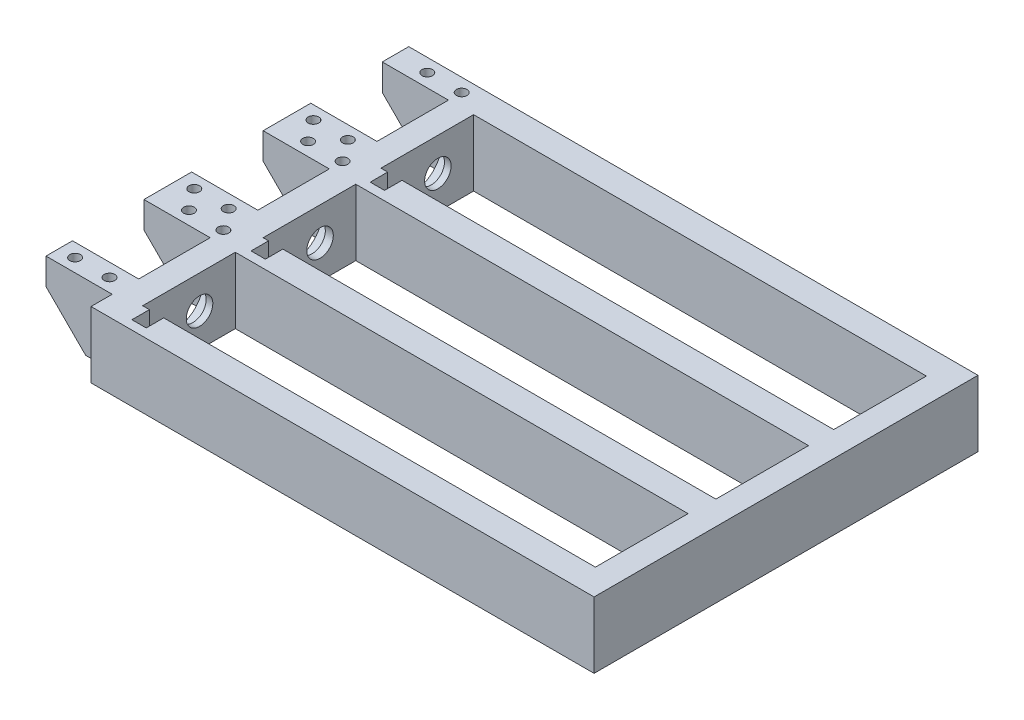
SolidWorks part; units mm, degrees
ref_plane "Płaszczyzna przednia" through (0, 0, 0) normal (0, 0, 1) x (1, 0, 0)
ref_plane "Płaszczyzna górna" through (0, 0, 0) normal (0, 1, 0) x (1, 0, 0)
ref_plane "Płaszczyzna prawa" through (0, 0, 0) normal (1, 0, 0) x (0, 0, -1)
sketch "Szkic1" plane through (0, 0, 0) normal (0, 1, 0) x (1, 0, 0)
  line L1 (-95, 72.5) -> (95, 72.5)
  line L2 (-95, 72.5) -> (-95, -72.5)
  line L3 (-95, -72.5) -> (95, -72.5)
  line L4 (95, 72.5) -> (95, -72.5)
  line L5 (-95, 72.5) -> (95, -72.5) construction
  line L6 (-95, -72.5) -> (95, 72.5) construction
  point P0 (0, 0)
  dimension "D1" = 145
  dimension "D2" = 190
extrude "Dodanie-wyciągnięcie1" add sketch "Szkic1" along normal blind 25
sketch "Szkic2" plane through (0, 25, 0) normal (0, 1, 0) x (1, 0, 0)
  line L0 (-95, 0) -> (95, 0) construction
  line L1 (-95, 72.5) -> (-95, -72.5) construction
  line L2 (95, -72.5) -> (95, 72.5) construction
  line L3 (0, 0) -> (0, -72.5) construction
  line L4 (-85, -17.5) -> (86, -17.5)
  line L5 (-85, -17.5) -> (-85, 17.5)
  line L6 (-85, 17.5) -> (86, 17.5)
  line L7 (86, -17.5) -> (86, 17.5)
  line L8 (-85, -17.5) -> (86, 17.5) construction
  line L9 (-85, 17.5) -> (86, -17.5) construction
  line L10 (-95, -72.5) -> (95, -72.5) construction
  line L11 (-85.5, 27.5) -> (85.5, 62.5) construction
  line L12 (-85.5, -62.5) -> (85.5, -62.5)
  line L13 (-85.5, -62.5) -> (-85.5, -27.5)
  line L14 (-85.5, -27.5) -> (85.5, -27.5)
  line L15 (85.5, -62.5) -> (85.5, -27.5)
  line L16 (-85.5, -62.5) -> (85.5, -27.5) construction
  line L17 (-85.5, -27.5) -> (85.5, -62.5) construction
  line L18 (-85.5, 62.5) -> (85.5, 27.5) construction
  line L19 (85.5, 62.5) -> (85.5, 27.5)
  line L20 (-85.5, 27.5) -> (85.5, 27.5)
  line L21 (-85.5, 62.5) -> (-85.5, 27.5)
  line L22 (-85.5, 62.5) -> (85.5, 62.5)
  point P6 (0.5, 0)
  point P15 (0, -45)
  point P24 (0, 45)
  dimension "D1" = 35
  dimension "D2" = 9
  dimension "D3" = 10
  dimension "D4" = 10
  dimension "D5" = 35
extrude "Wytnij-wyciągnięcie1" cut sketch "Szkic2" against normal blind 50
sketch "Szkic3" plane through (85.5, 0, 0) normal (-1, 0, 0) x (0, 0, 1)
  line L0 (27.5, 12.5) -> (62.5, 12.5) construction
  line L1 (27.5, 0) -> (27.5, 25) construction
  line L2 (62.5, 0) -> (62.5, 25) construction
  circle A0 centre (41, 12.5) radius 11
  dimension "D1" = 22
  dimension "D2" = 13.5
extrude "Wytnij-wyciągnięcie2" cut sketch "Szkic3" against normal blind 7
sketch "Szkic4" plane through (-95, 0, 0) normal (-1, 0, 0) x (0, 0, 1)
  circle A0 centre (41, 12.5) radius 11 construction
  circle A1 centre (41, 12.5) radius 11
extrude "Wytnij-wyciągnięcie3" cut sketch "Szkic4" against normal blind 7
sketch "Szkic5" plane through (-88, 0, 0) normal (-1, 0, 0) x (0, 0, 1)
  circle A0 centre (41, 12.5) radius 5
  dimension "D1" = 10
extrude "Wytnij-wyciągnięcie4" cut sketch "Szkic5" against normal blind 7
sketch "Szkic7" plane through (0, 25, 0) normal (0, 1, 0) x (1, 0, 0)
  line L0 (-95, 72.5) -> (-95, -72.5) construction
  line L1 (-95, -64.5) -> (-120, -64.5)
  line L2 (-95, -64.5) -> (-95, -54.5)
  line L3 (-95, -54.5) -> (-120, -54.5)
  line L4 (-120, -64.5) -> (-120, -54.5)
  line L6 (-95, -27.5) -> (-120, -27.5)
  line L7 (-95, -27.5) -> (-95, -17.5)
  line L8 (-95, -17.5) -> (-120, -17.5)
  line L9 (-120, -27.5) -> (-120, -17.5)
  line L10 (-85.5, -46) -> (-85.5, -36) construction
  line L11 (-85.5, -41) -> (-183.1039, -41) construction
  line L12 (-95, -27.5) -> (-95, -54.5) construction
  line L13 (95, -72.5) -> (95, 72.5) construction
  line L14 (-85.5, -46) -> (-85.5, -36)
  line L15 (-85.5, -41) -> (95, -41) construction
  point P14 (-95, -41)
  line M24 (-95, 72.5) -> (-95, -72.5)
  dimension "D1" = 27
  dimension "D2" = 10
  dimension "D3" = 215
extrude "Dodanie-wyciągnięcie2" add sketch "Szkic7" against normal up to vertex (25 mm away) contours L9 L6 L8 M24 | L4 L1 L3 M24 up to point (-95, 0, 72.5)
sketch "Szkic8" plane through (0, 25, 0) normal (0, 1, 0) x (1, 0, 0)
  line L0 (-120, -59.5) -> (-114, -59.5) construction
  line L1 (-120, -64.5) -> (-120, -54.5) construction
  line L3 (-95, -41) -> (-185.7611, -41) construction
  line L4 (-95, -27.5) -> (-95, -54.5) construction
  line L5 (-114, -59.5) -> (-101, -59.5) construction
  line L6 (-120, -22.5) -> (-108, -22.5) construction
  line L7 (-120, -27.5) -> (-120, -17.5) construction
  line L8 (-108, -22.5) -> (-95, -22.5) construction
  circle A0 centre (-114, -59.5) radius 2
  circle A1 centre (-101, -59.5) radius 2
  circle A6 centre (-108, -22.5) radius 2
  circle A7 centre (-95, -22.5) radius 2
  dimension "D2" = 13
  dimension "D3" = 6
  dimension "D1" = 4
  dimension "D4" = 13
  dimension "D5" = 12
extrude "Wytnij-wyciągnięcie5" cut sketch "Szkic8" against normal blind 12
sketch "Szkic10" plane through (0, 25, 0) normal (0, 1, 0) x (1, 0, 0)
  line L0 (-82.45, -66.4) -> (-82.95, -66.4) construction
  line L1 (-85.5, -62.5) -> (85.5, -62.5) construction
  line L7 (-80.25, -66.4) -> (-80.25, -60.0836) construction
  line L8 (-80.25, -69.1) -> (-80.25, -68.6) construction
  line L9 (-77.55, -62.5) -> (-82.95, -62.5)
  line L10 (-77.55, -62.5) -> (-77.55, -69.1)
  line L11 (-77.55, -69.1) -> (-82.95, -69.1)
  line L12 (-82.95, -62.5) -> (-82.95, -69.1)
  line L13 (-77.55, -62.5) -> (-82.95, -69.1) construction
  line L14 (-78.05, -62.35) -> (-78.05, -58.85)
  line L15 (-78.05, -58.85) -> (-82.45, -58.85)
  line L16 (-82.45, -58.85) -> (-82.45, -62.35)
  line L17 (-82.45, -62.35) -> (-81.075, -62.35)
  line L18 (-81.075, -62.35) -> (-81.075, -64.3605)
  line L19 (-79.425, -64.3605) -> (-79.425, -62.35)
  line L20 (-79.425, -62.35) -> (-78.05, -62.35)
  line L21 (-77.55, -69.1) -> (-82.95, -62.5) construction
  arc A2 (-81.075, -64.3605) -> (-79.425, -64.3605) centre (-80.25, -66.4) ccw
  point P4 (-80.25, -65.8)
  line M52 (85.5, -62.5) -> (-85.5, -62.5)
  dimension "D2" = 2.2
  dimension "D1" = 80.25
  dimension "D3" = 0.5
  dimension "D4" = 66.4
  dimension "D5" = 0.5
extrude "Wytnij-wyciągnięcie6" cut sketch "Szkic10" against normal blind 40 contours A2 L18 L9 L12 L11 L10 L19 M52 | L18 A2 L19 L9
pattern_linear "Szyk liniowy1" count 3 spacing 45 along (0, 0, -1) of "Wytnij-wyciągnięcie5", "Dodanie-wyciągnięcie2", "Wytnij-wyciągnięcie4", "Wytnij-wyciągnięcie3", "Wytnij-wyciągnięcie2", "Wytnij-wyciągnięcie6"
chamfer "Sfazowanie1" distance 15 angle 45 4 edges at (-120, 0, 59.5) (-120, 0, 18.5) (-120, 0, -26.5) (-120, 0, -67.5)
